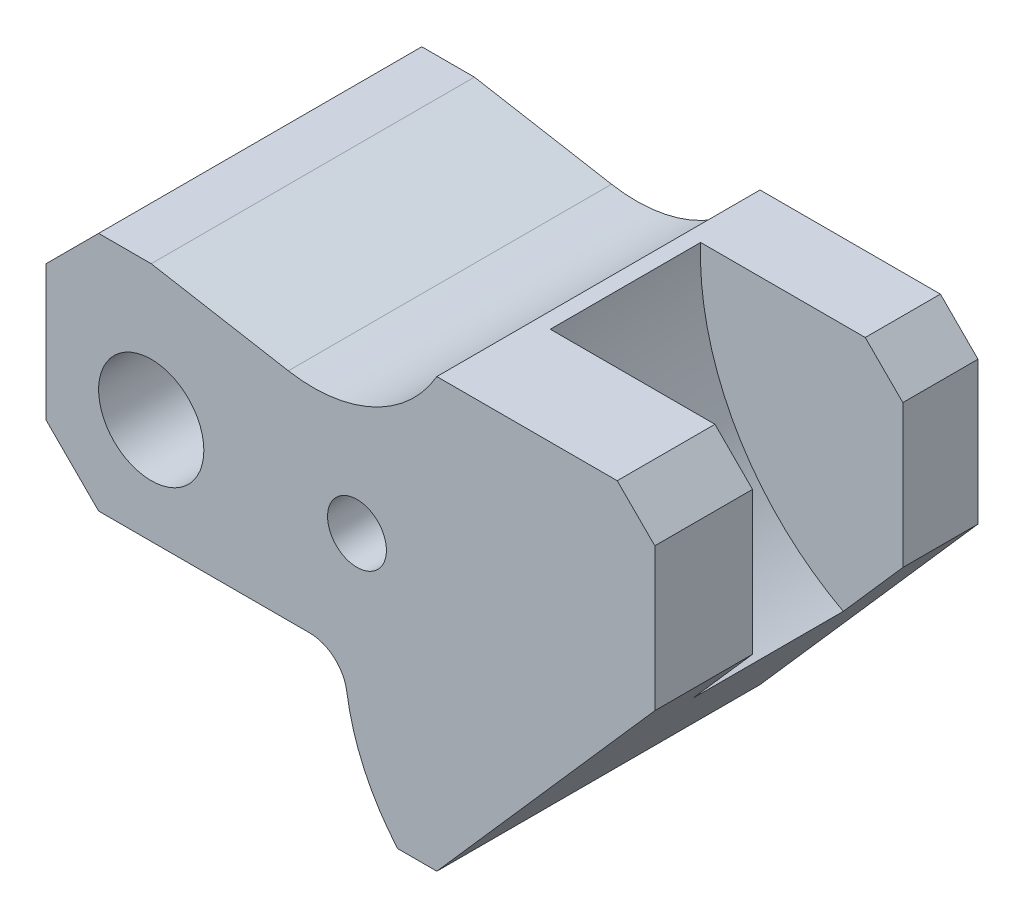
SolidWorks part; units mm, degrees
material "AISI 1020"
ref_plane "Front Plane" through (0, 0, 0) normal (0, 0, 1) x (1, 0, 0)
ref_plane "Top Plane" through (0, 0, 0) normal (0, 1, 0) x (1, 0, 0)
ref_plane "Right Plane" through (0, 0, 0) normal (1, 0, 0) x (0, 0, -1)
sketch "Sketch1" plane through (0, 0, 0) normal (0, 0, 1) x (1, 0, 0)
  line L0 (-14, -7) -> (-14, 11)
  line L1 (-14, 11) -> (-7, 18)
  line L2 (-7, 18) -> (0, 18)
  line L3 (0, 18) -> (18.2431, 14.7833)
  line L4 (38, 24) -> (62, 24)
  line L5 (62, 24) -> (67, 19)
  line L6 (67, 19) -> (67, 0)
  line L7 (67, 0) -> (38, -33)
  line L8 (38, -33) -> (32.7881, -33)
  line L9 (-14, -7) -> (-7, -14)
  line L10 (-7, -14) -> (21.0666, -14)
  circle A0 centre (0, 0) radius 7
  arc A1 (18.2431, 14.7833) -> (38, 24) centre (21.5424, 33.4946) ccw
  arc A2 (21.0666, -14) -> (26.0123, -18.2647) centre (21.0666, -19) cw
  arc A3 (26.0123, -18.2647) -> (32.7881, -33) centre (54.697, -14) ccw
  dimension "D2" = 14
  dimension "D8" = 5
  dimension "D9" = 29
  dimension "D17" = 19
  dimension "D1" = 32
  dimension "D3" = 14
  dimension "D4" = 7
  dimension "D5" = 14
  dimension "D6" = 45
  dimension "D7" = 29
  dimension "D10" = 81
  dimension "D11" = 57
  dimension "D12" = 10
  dimension "D13" = 19
  dimension "D14" = 14
  dimension "D15" = 45
  dimension "D16" = 7
  dimension "D18" = 5
  dimension "D19" = 24
  dimension "D20" = 19
  dimension "D21" = 29
extrude "Boss-Extrude1" add sketch "Sketch1" along normal blind 43
sketch "Sketch2" plane through (0, 0, 0) normal (0, 0, -1) x (-1, 0, 0)
  circle A0 centre (-75.9386, 22.6383) radius 35.8686
extrude "Cut-Extrude1" cut sketch "Sketch2" against normal blind 20 from offset 10 offset against normal yes
sketch "Sketch3" plane through (0, 0, 43) normal (0, 0, 1) x (1, 0, 0)
  circle A0 centre (27.3749, 0.6184) radius 3.9177
extrude "Cut-Extrude2" cut sketch "Sketch3" against normal offset from surface (23 mm away) 20 up to face at (23.5218, 0.4885, 0)
equation "\"A\"=81"
equation "\"D10@Sketch1\"=\"A\""
equation "\"B\"=57"
equation "\"D11@Sketch1\"=\"B\""
equation "\"C\"=43"
equation "\"D1@Boss-Extrude1\"=\"C\""
